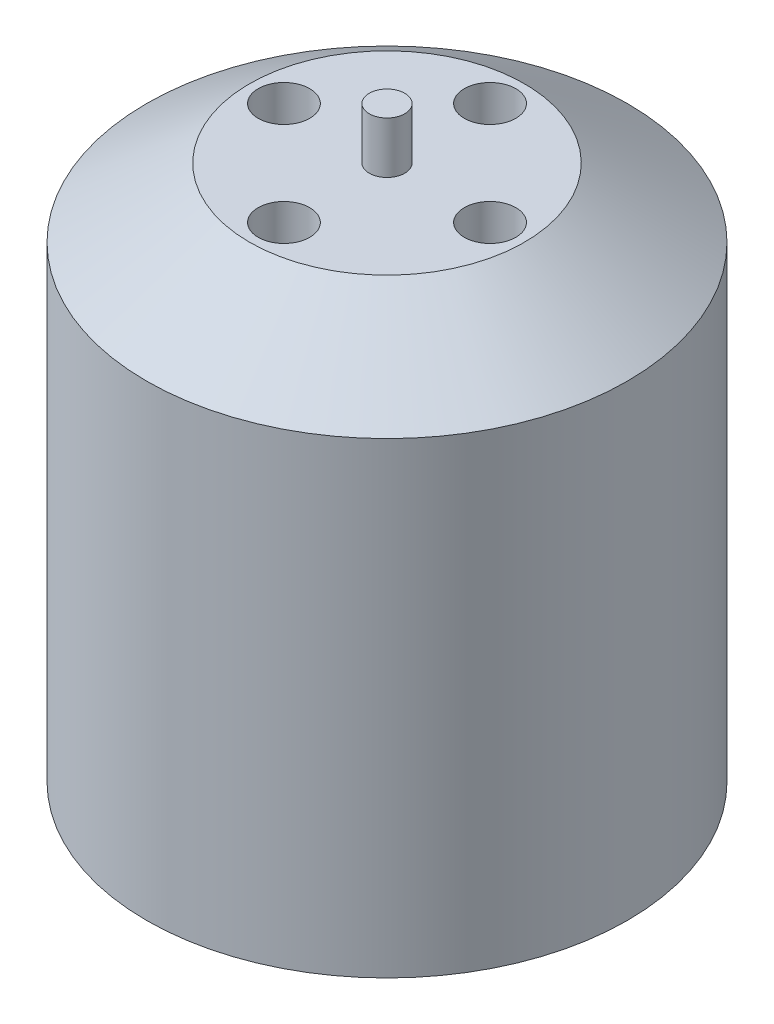
SolidWorks part; units mm, degrees
ref_plane "Ebene vorne" through (0, 0, 0) normal (0, 0, 1) x (1, 0, 0)
ref_plane "Ebene oben" through (0, 0, 0) normal (0, 1, 0) x (1, 0, 0)
ref_plane "Ebene rechts" through (0, 0, 0) normal (1, 0, 0) x (0, 0, -1)
sketch "Skizze1" plane through (0, 0, 0) normal (0, 1, 0) x (1, 0, 0)
  circle A0 centre (0, 0) radius 14
  dimension "D1" = 28
extrude "Aufsatz-Linear austragen1" add sketch "Skizze1" along normal blind 31.2
chamfer "Fase1" distance 4 distance2 6 1 edges at (0, 31.2, 14)
sketch "Skizze2" plane through (0, 31.2, 0) normal (0, 1, 0) x (1, 0, 0)
  circle A0 centre (0, 0) radius 1.0337
extrude "Aufsatz-Linear austragen2" add sketch "Skizze2" along normal blind 3
sketch "Skizze3" plane through (0, 31.2, 0) normal (0, 1, 0) x (1, 0, 0)
  line L0 (0, -6) -> (0, 6)
  line L1 (-6, 0) -> (6, 0)
  circle A0 centre (-6, 0) radius 1.5
  circle A1 centre (0, 6) radius 1.5
  circle A2 centre (6, 0) radius 1.5
  circle A3 centre (0, -6) radius 1.5
  point P5 (0, 0)
  point P9 (0, 0)
  dimension "D3" = 3
  dimension "D4" = 3
  dimension "D5" = 3
  dimension "D6" = 3
  dimension "D1" = 12
  dimension "D2" = 12
extrude "Schnitt-Linear austragen1" cut sketch "Skizze3" against normal blind 3
sketch "Skizze4" plane through (0, 0, 0) normal (0, -1, 0) x (1, 0, 0)
  circle A0 centre (0, 0) radius 3.1
  dimension "D1" = 6.2
extrude "Aufsatz-Linear austragen3" add sketch "Skizze4" along normal blind 3
sketch "Skizze5" plane through (0, 0, 0) normal (0, -1, 0) x (1, 0, 0)
  line L0 (-9.5, 0) -> (9.5, 0) construction
  line L1 (0, -8) -> (0, 8) construction
  circle A0 centre (0, 8) radius 1.5
  circle A1 centre (-9.5, 0) radius 1.5
  circle A2 centre (9.5, 0) radius 1.5
  circle A3 centre (0, -8) radius 1.5
  point P5 (0, 0)
  point P9 (0, 0)
  dimension "D3" = 3
  dimension "D4" = 3
  dimension "D5" = 3
  dimension "D6" = 3
  dimension "D1" = 16
  dimension "D2" = 19
extrude "Schnitt-Linear austragen2" cut sketch "Skizze5" against normal blind 3
sketch "Skizze6" plane through (0, 31.2, 0) normal (0, 1, 0) x (1, 0, 0)
  circle A0 centre (0, 0) radius 40.7596
  circle A1 centre (0, -59.7596) radius 19 construction
sketch "Skizze7" plane through (0, 0, 0) normal (0, -1, 0) x (1, 0, 0)
  line L0 (0, -8) -> (9.5, 0)
  line L1 (0, 8) -> (-9.5, 0)
